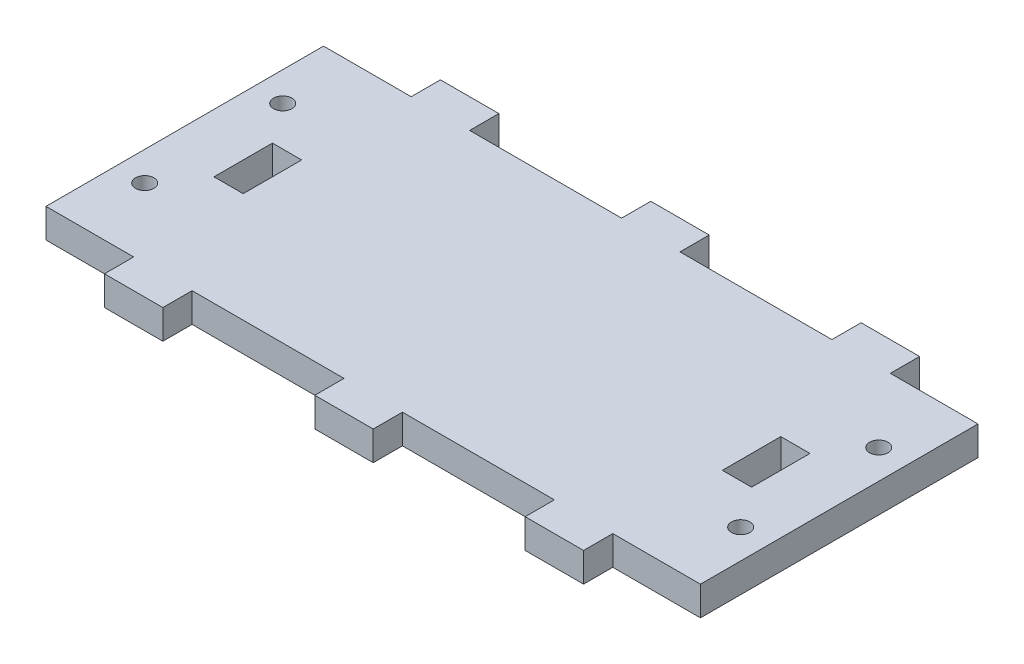
SolidWorks part; units mm, degrees
ref_plane "Front Plane" through (0, 0, 0) normal (0, 0, 1) x (1, 0, 0)
ref_plane "Top Plane" through (0, 0, 0) normal (0, 1, 0) x (1, 0, 0)
ref_plane "Right Plane" through (0, 0, 0) normal (1, 0, 0) x (0, 0, -1)
sketch "Sketch1" plane through (0, 0, 0) normal (0, 1, 0) x (1, 0, 0)
  line L1 (0, 0) -> (142.24, 0)
  line L2 (0, 0) -> (0, -60.325)
  line L3 (0, -60.325) -> (142.24, -60.325)
  line L4 (142.24, 0) -> (142.24, -60.325)
  dimension "D1" = 60.325
  dimension "D2" = 142.24
extrude "Boss-Extrude1" add sketch "Sketch1" along normal blind 6.35
sketch "Sketch2" plane through (0, 6.35, 0) normal (0, 1, 0) x (1, 0, 0)
  line L0 (0, 0) -> (0, -60.325) construction
  line L1 (6.35, -45.225) -> (6.35, -15.225) construction
  line L2 (142.24, 0) -> (0, 0) construction
  line L3 (71.12, -60.325) -> (71.12, 0) construction
  line L4 (0, -60.325) -> (142.24, -60.325) construction
  line L5 (135.89, -45.225) -> (135.89, -15.225) construction
  line L14 (12.7, -60.325) -> (12.7, 4.3594) construction
  line L15 (129.54, -23.8125) -> (123.19, -23.8125)
  line L16 (12.7, -36.5125) -> (19.05, -36.5125)
  line L17 (12.7, -36.5125) -> (12.7, -23.8125)
  line L18 (12.7, -23.8125) -> (19.05, -23.8125)
  line L19 (19.05, -36.5125) -> (19.05, -23.8125)
  line L20 (123.19, -36.5125) -> (123.19, -23.8125)
  line L21 (129.54, -36.5125) -> (123.19, -36.5125)
  line L22 (129.54, -36.5125) -> (129.54, -23.8125)
  circle A0 centre (6.35, -15.225) radius 2
  circle A1 centre (6.35, -45.225) radius 2
  circle A2 centre (135.89, -45.225) radius 2
  circle A3 centre (135.89, -15.225) radius 2
  point P2 (0, -30.1625)
  point P21 (15.875, -36.5125)
  dimension "D1" = 4
  dimension "D2" = 30
  dimension "D3" = 6.35
  dimension "D4" = 15.1
  dimension "D5" = 12.7
  dimension "D6" = 12.7
  dimension "D7" = 6.35
  dimension "D8" = 6.35
extrude "Cut-Extrude1" cut sketch "Sketch2" against normal through all
sketch "Sketch3" plane through (0, 6.35, 0) normal (0, 1, 0) x (1, 0, 0)
  line L0 (142.24, 0) -> (0, 0) construction
  line L1 (19.05, 0) -> (31.75, 0)
  line L2 (19.05, 0) -> (19.05, 6.35)
  line L3 (19.05, 6.35) -> (31.75, 6.35)
  line L4 (31.75, 0) -> (31.75, 6.35)
  line L5 (0, 0) -> (0, -60.325) construction
  line L6 (0, -30.1625) -> (142.24, -30.1625) construction
  line L7 (142.24, -60.325) -> (142.24, 0) construction
  line L8 (0, -60.325) -> (142.24, -60.325) construction
  line L9 (71.12, -60.325) -> (71.12, 0) construction
  line L10 (123.19, 0) -> (123.19, 6.35)
  line L11 (110.49, 0) -> (110.49, 6.35)
  line L12 (123.19, 0) -> (110.49, 0)
  line L13 (123.19, 6.35) -> (110.49, 6.35)
  line L14 (123.19, -60.325) -> (123.19, -66.675)
  line L15 (110.49, -60.325) -> (110.49, -66.675)
  line L16 (123.19, -60.325) -> (110.49, -60.325)
  line L17 (123.19, -66.675) -> (110.49, -66.675)
  line L18 (31.75, -60.325) -> (31.75, -66.675)
  line L19 (19.05, -60.325) -> (31.75, -60.325)
  line L20 (19.05, -60.325) -> (19.05, -66.675)
  line L21 (19.05, -66.675) -> (31.75, -66.675)
  line L22 (77.47, -60.325) -> (77.47, -66.675)
  line L23 (64.77, 0) -> (77.47, 0)
  line L24 (64.77, 0) -> (64.77, 6.35)
  line L25 (64.77, 6.35) -> (77.47, 6.35)
  line L26 (77.47, 0) -> (77.47, 6.35)
  line L27 (64.77, -60.325) -> (77.47, -60.325)
  line L28 (64.77, -60.325) -> (64.77, -66.675)
  line L29 (64.77, -66.675) -> (77.47, -66.675)
  dimension "D1" = 19.05
  dimension "D2" = 12.7
  dimension "D3" = 6.35
  dimension "D4" = 6.35
  dimension "D5" = 12.7
  dimension "D6" = 6.35
extrude "Boss-Extrude2" add sketch "Sketch3" against normal blind 6.35
